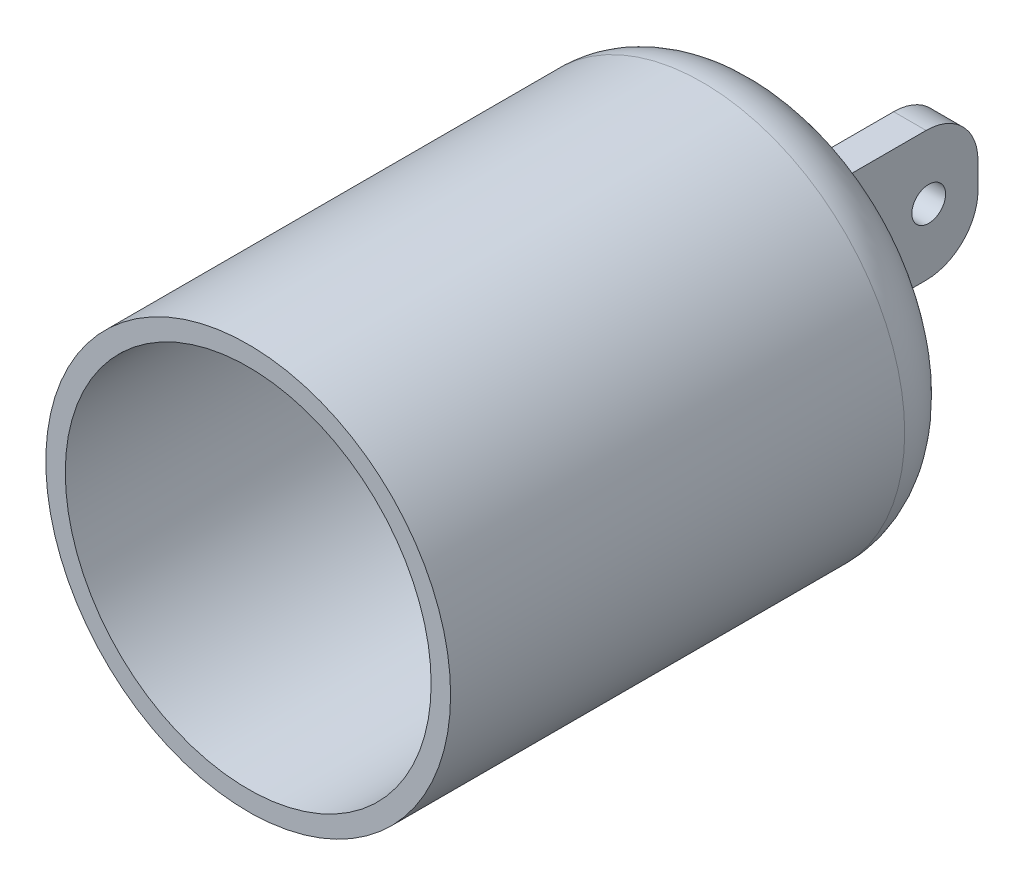
SolidWorks part; units mm, degrees
ref_plane "Front Plane" through (0, 0, 0) normal (0, 0, 1) x (1, 0, 0)
ref_plane "Top Plane" through (0, 0, 0) normal (0, 1, 0) x (1, 0, 0)
ref_plane "Right Plane" through (0, 0, 0) normal (1, 0, 0) x (0, 0, -1)
sketch "Sketch1" plane through (0, 0, 0) normal (0, 0, 1) x (1, 0, 0)
  circle A0 centre (0, 0) radius 136 construction
  circle A1 centre (0, 0) radius 141 construction
  circle A2 centre (0, 0) radius 156
  dimension "D1" = 272
  dimension "D2" = 5
  dimension "D3" = 15
extrude "Boss-Extrude1" add sketch "Sketch1" along normal blind 400
sketch "Sketch2" plane through (0, 0, 0) normal (0, 0, -1) x (-1, 0, 0)
  line L1 (12.5, -50) -> (-12.5, -50)
  line L2 (12.5, -50) -> (12.5, 50)
  line L3 (12.5, 50) -> (-12.5, 50)
  line L4 (-12.5, -50) -> (-12.5, 50)
  line L5 (12.5, -50) -> (-12.5, 50) construction
  line L6 (12.5, 50) -> (-12.5, -50) construction
  point P0 (0, 0)
  dimension "D1" = 25
  dimension "D2" = 100
extrude "Boss-Extrude2" add sketch "Sketch2" along normal blind 150
sketch "Sketch3" plane through (12.5, 0, 0) normal (1, 0, 0) x (0, 0, -1)
  line L0 (112, 0) -> (150, 0) construction
  line L1 (150, 50) -> (150, -50) construction
  line L2 (125, 0) -> (125, 50) construction
  line L3 (150, 50) -> (0, 50) construction
  circle A0 centre (112, 0) radius 13
  dimension "D1" = 26
  dimension "D2" = 25
extrude "Cut-Extrude1" cut sketch "Sketch3" against normal through all
fillet "Fillet1" radius 40 2 edges at (0, 50, -150) (0, -50, -150)
fillet "Fillet3" radius 20 4 edges at (-12.5, 0, 0) (0, -50, 0) (12.5, 0, 0) (0, 50, 0)
fillet "Fillet4" radius 50 1 edges at (156, 0, 0)
shell "Shell1" thickness 15
